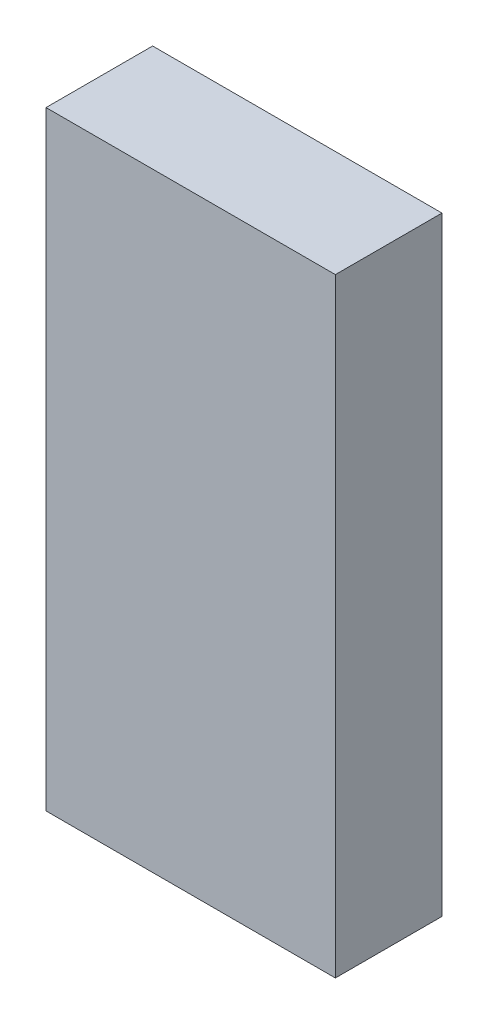
SolidWorks part; units mm, degrees
ref_plane "Front Plane" through (0, 0, 0) normal (0, 0, 1) x (1, 0, 0)
ref_plane "Top Plane" through (0, 0, 0) normal (0, 1, 0) x (1, 0, 0)
ref_plane "Right Plane" through (0, 0, 0) normal (1, 0, 0) x (0, 0, -1)
sketch "Sketch1" plane through (0, 0, 0) normal (0, 0, 1) x (1, 0, 0)
  line L1 (-9.5, 20) -> (9.5, 20)
  line L2 (-9.5, 20) -> (-9.5, -20)
  line L3 (-9.5, -20) -> (9.5, -20)
  line L4 (9.5, 20) -> (9.5, -20)
  line L5 (-9.5, 20) -> (9.5, -20) construction
  line L6 (-9.5, -20) -> (9.5, 20) construction
  point P0 (0, 0)
  dimension "D1" = 19
  dimension "D2" = 40
extrude "Boss-Extrude1" add sketch "Sketch1" along normal blind 7
